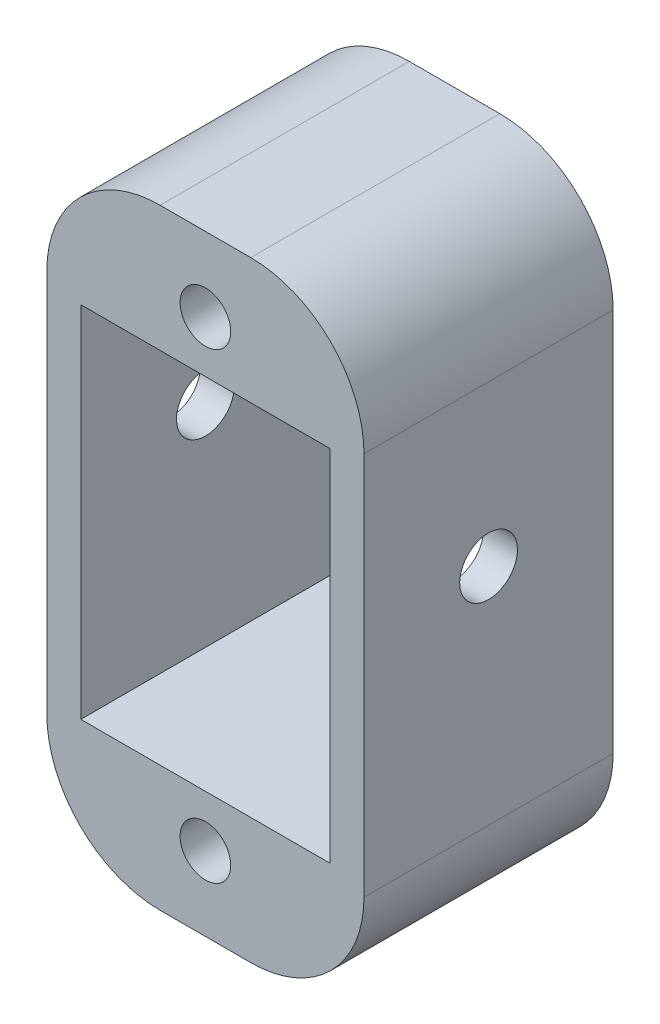
SolidWorks part; units mm, degrees
ref_plane "Спереди" through (0, 0, 0) normal (0, 0, 1) x (1, 0, 0)
ref_plane "Сверху" through (0, 0, 0) normal (0, 1, 0) x (1, 0, 0)
ref_plane "Справа" through (0, 0, 0) normal (1, 0, 0) x (0, 0, -1)
sketch "Эскиз1" plane through (0, 0, 0) normal (0, 0, 1) x (1, 0, 0)
  line L0 (-0.1141, 26.1482) -> (-0.1141, -25.4637) construction
  circle A0 centre (-0.1141, 19.8058) radius 2.2352
  circle A1 centre (-0.1141, -21.0042) radius 2.2352
  dimension "D1" = 40.81
sketch "Эскиз2" plane through (0, 0, 0) normal (0, 0, 1) x (1, 0, 0)
  line L0 (-11.1141, 15.2558) -> (10.8859, 15.2558) construction
  line L1 (-0.1141, 26.1482) -> (-0.1141, -25.4637) construction
  line L2 (-11.1141, 12.2558) -> (10.8859, 12.2558) construction
  line L3 (-11.1141, 12.2558) -> (-11.1141, -5.7442) construction
  line L4 (-11.1141, -5.7442) -> (10.8859, -5.7442) construction
  line L5 (-11.1141, -8.7442) -> (10.8859, -8.7442) construction
  line L6 (-14.9989, 3.2558) -> (19.4647, 3.2558) construction
  line L7 (-11.1141, 15.2558) -> (10.8859, 15.2558)
  line L8 (10.8859, 15.2558) -> (10.8859, -16.4542)
  line L9 (10.8859, -16.4542) -> (-11.1141, -16.4542)
  line L10 (-11.1141, -16.4542) -> (-11.1141, 15.2558)
  line L12 (-4.1141, 26.3558) -> (3.8859, 26.3558)
  line L13 (-14.1141, 16.3558) -> (-14.1141, -17.5542)
  line L14 (-4.1141, -27.5542) -> (3.8859, -27.5542)
  line L15 (13.8859, 16.3558) -> (13.8859, -17.5542)
  circle A0 centre (-0.1141, 19.8058) radius 2.2352 construction
  circle A1 centre (-0.1141, -21.0042) radius 2.2352 construction
  arc A2 (3.8859, -27.5542) -> (13.8859, -17.5542) centre (3.8859, -17.5542) ccw
  arc A3 (-14.1141, -17.5542) -> (-4.1141, -27.5542) centre (-4.1141, -17.5542) ccw
  arc A4 (3.8859, 26.3558) -> (13.8859, 16.3558) centre (3.8859, 16.3558) cw
  arc A5 (-4.1141, 26.3558) -> (-14.1141, 16.3558) centre (-4.1141, 16.3558) ccw
  dimension "D7" = 4.55
  dimension "D10" = 6.55
  dimension "D12" = 10
  dimension "D1" = 4.55
  dimension "D2" = 11
  dimension "D3" = 11
  dimension "D4" = 3
  dimension "D5" = 18
  dimension "D6" = 3
  dimension "D8" = 3
  dimension "D9" = 3
  dimension "D11" = 6.55
extrude "Бобышка-Вытянуть1" add sketch "Эскиз2" along normal blind 22
extrude "Вырез-Вытянуть1" cut sketch "Эскиз1" along normal through all
sketch "Эскиз3" plane through (13.8859, 0, 0) normal (1, 0, 0) x (0, 0, -1)
  line L0 (-11, 21.125) -> (-11, -14.7672) construction
  line L2 (-22, 26.3558) -> (0, 26.3558) construction
  circle A0 centre (-11, 2.2558) radius 2.55
  dimension "D1" = 5.1
  dimension "D2" = 24.1
extrude "Вырез-Вытянуть2" cut sketch "Эскиз3" against normal through all both and the other way through all
